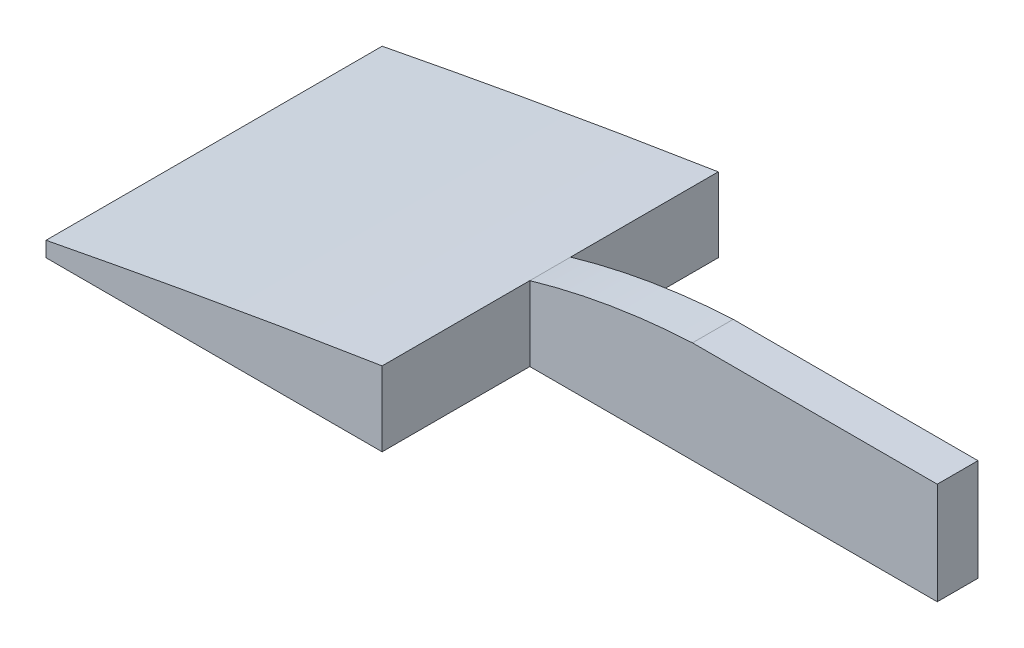
SolidWorks part; units mm, degrees
ref_plane "Plan de face" through (0, 0, 0) normal (0, 0, 1) x (1, 0, 0)
ref_plane "Plan de dessus" through (0, 0, 0) normal (0, 1, 0) x (1, 0, 0)
ref_plane "Plan de droite" through (0, 0, 0) normal (1, 0, 0) x (0, 0, -1)
sketch "Esquisse2" plane through (0, 0, 0) normal (0, 1, 0) x (1, 0, 0)
  line L0 (0, 9.25) -> (0, 2) construction
  line L1 (0, 0) -> (20, 0)
  line L2 (0, 0) -> (0, 2)
  line L3 (0, 2) -> (20, 2)
  line L4 (20, 0) -> (20, 2)
  line L5 (0, -7.25) -> (-16.5, -7.25)
  line L6 (0, -7.25) -> (0, 9.25)
  line L7 (0, 9.25) -> (-16.5, 9.25)
  line L8 (-16.5, -7.25) -> (-16.5, 9.25)
  line L9 (0, -7.25) -> (0, 0) construction
  dimension "D1" = 2
  dimension "D2" = 20
  dimension "D3" = 16.5
  dimension "D4" = 16.5
extrude "Boss.-Extru.1" add sketch "Esquisse2" along normal blind 5 contours L6 L5 L8 L7 | L2 L1 L4 L3
sketch "Esquisse3" plane through (0, 0, -9.25) normal (0, 0, -1) x (-1, 0, 0)
  line L0 (16.5, 5) -> (16.5, 0) construction
  line L1 (0, 5) -> (0, 3.6541)
  line L2 (0, 5) -> (0, 0) construction
  line L3 (0, 5) -> (3.5989, 6.4622)
  line L4 (3.5989, 6.4622) -> (16.723, 6.2386)
  line L5 (16.723, 6.2386) -> (18.6885, 4.2049)
  line L6 (18.6885, 4.2049) -> (16.5, 0.7444)
  spline S1 degree 3 poles (16.8474, 0.7869) (10.6265, 1.8666) (4.4022, 2.9267) (-1.8271, 3.9572) knots 0 0 0 0 1 1 1 1 construction
  spline S2 degree 2 poles (0, 3.6541) (8.2763, 2.347) (16.5, 0.7444) knots 0 0 0 1 1 1
extrude "Enlèv. mat.-Extru.1" cut sketch "Esquisse3" against normal blind 17
sketch "Esquisse4" plane through (0, 0, 0) normal (0, 0, 1) x (1, 0, 0)
  line L0 (0, 5) -> (20, 5) construction
  line L1 (0, 3.6541) -> (0, 5)
  line L2 (0, 5) -> (7.9836, 5)
  spline S0 degree 2 poles (0, 3.6541) (3.9079, 4.793) (7.9836, 5) knots 0 0 0 1 1 1
extrude "Enlèv. mat.-Extru.2" cut sketch "Esquisse4" against normal blind 17
